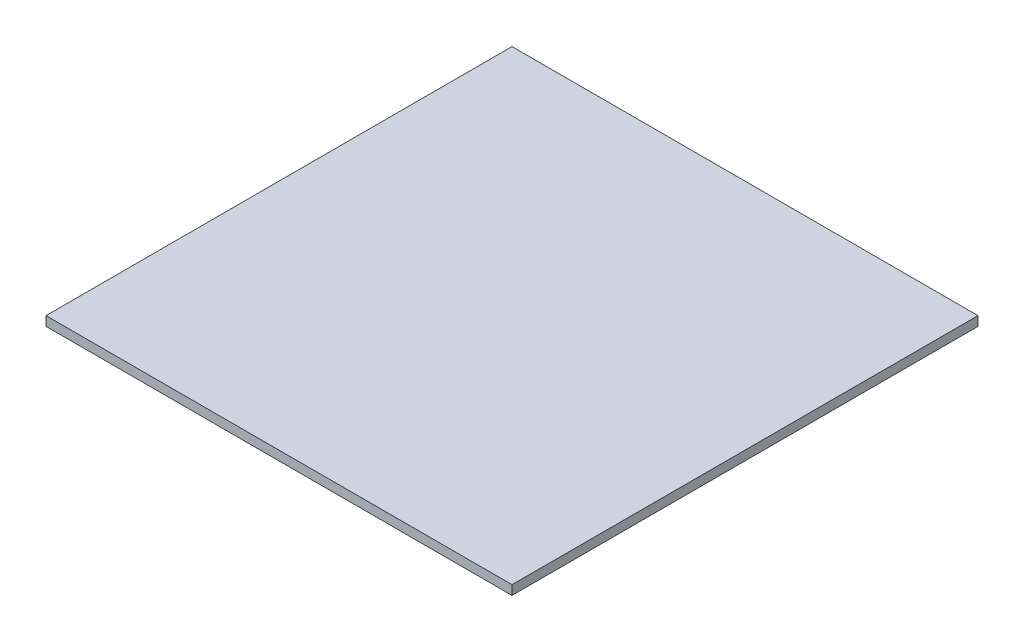
SolidWorks part; units mm, degrees
ref_plane "Front Plane" through (0, 0, 0) normal (0, 0, 1) x (1, 0, 0)
ref_plane "Top Plane" through (0, 0, 0) normal (0, 1, 0) x (1, 0, 0)
ref_plane "Right Plane" through (0, 0, 0) normal (1, 0, 0) x (0, 0, -1)
sketch "Sketch1" plane through (0, 0, 0) normal (0, 1, 0) x (1, 0, 0)
  line L1 (-50, 50) -> (50, 50)
  line L2 (-50, 50) -> (-50, -50)
  line L3 (-50, -50) -> (50, -50)
  line L4 (50, 50) -> (50, -50)
  line L5 (-50, 50) -> (50, -50) construction
  line L6 (-50, -50) -> (50, 50) construction
  point P0 (0, 0)
  dimension "D1" = 100
  dimension "D2" = 100
extrude "Boss-Extrude1" add sketch "Sketch1" along normal blind 2
